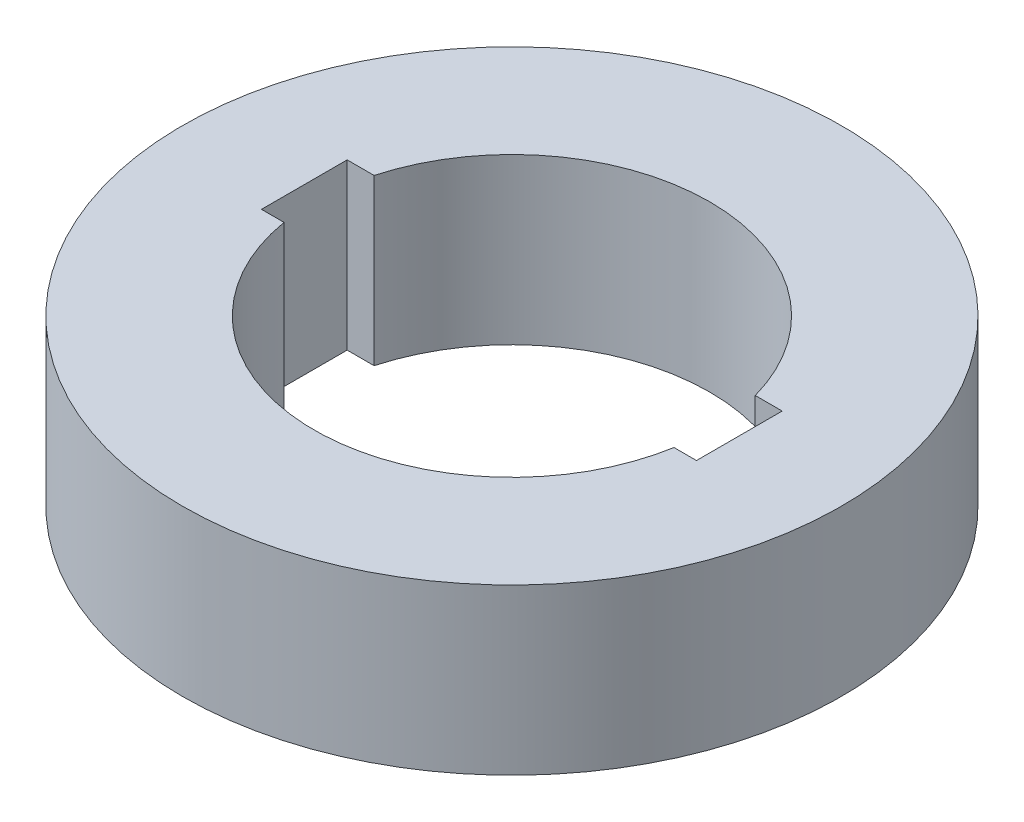
SolidWorks part; units mm, degrees
ref_plane "Front Plane" through (0, 0, 0) normal (0, 0, 1) x (1, 0, 0)
ref_plane "Top Plane" through (0, 0, 0) normal (0, 1, 0) x (1, 0, 0)
ref_plane "Right Plane" through (0, 0, 0) normal (1, 0, 0) x (0, 0, -1)
sketch "Sketch2" plane through (0, 0, 0) normal (0, 1, 0) x (1, 0, 0)
  circle A0 centre (0, 0) radius 30
  circle A1 centre (0, 0) radius 50
  dimension "D1" = 100
  dimension "D2" = 60
extrude "Boss-Extrude1" add sketch "Sketch2" along normal blind 25
sketch "Sketch3" plane through (0, 25, 0) normal (0, 1, 0) x (1, 0, 0)
  line L1 (-33, 8) -> (33, 8)
  line L2 (-33, 8) -> (-33, -5)
  line L3 (-33, -5) -> (33, -5)
  line L4 (33, 8) -> (33, -5)
  dimension "D1" = 66
  dimension "D2" = 33
  dimension "D3" = 13
  dimension "D4" = 8
extrude "Cut-Extrude1" cut sketch "Sketch3" against normal blind 25
